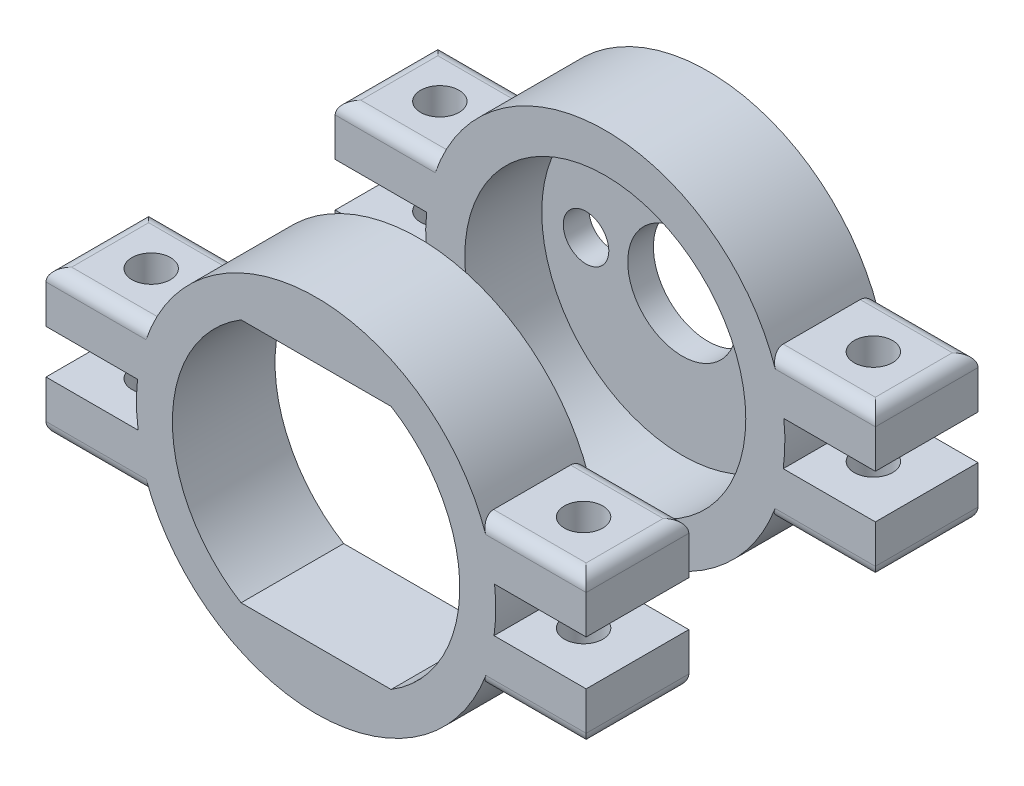
SolidWorks part; units mm, degrees
ref_plane "Alzado" through (0, 0, 0) normal (0, 0, 1) x (1, 0, 0)
ref_plane "Planta" through (0, 0, 0) normal (0, 1, 0) x (1, 0, 0)
ref_plane "Vista lateral" through (0, 0, 0) normal (1, 0, 0) x (0, 0, -1)
sketch "Croquis1" plane through (0, 0, 0) normal (0, 0, 1) x (1, 0, 0)
  line L0 (0, 1.5054) -> (0, -1.9098) construction
  line L1 (-13.9188, 1.5054) -> (-24.0497, 1.5054)
  line L2 (-24.0497, 1.5054) -> (-24.0497, 5.5054)
  line L3 (-13.8691, -1.9098) -> (-24, -1.9098)
  line L4 (-24.0497, 5.5054) -> (-12.8697, 5.5054)
  line L5 (-24, -1.9098) -> (-24, -5.9098)
  line L6 (-24, -5.9098) -> (-12.82, -5.9098)
  line L7 (24, -5.9098) -> (12.82, -5.9098)
  line L8 (24.0497, 5.5054) -> (12.8697, 5.5054)
  line L9 (13.8691, -1.9098) -> (24, -1.9098)
  line L10 (13.9188, 1.5054) -> (24.0143, 1.5054)
  line L11 (24, -1.9098) -> (24, -5.9098)
  line L12 (24.0143, 1.5054) -> (24.0497, 5.5054)
  arc A0 (12.8697, 5.5054) -> (-12.8697, 5.5054) centre (0, 0) ccw
  arc A1 (-13.9188, 1.5054) -> (-13.8691, -1.9098) centre (0, 0) ccw
  arc A2 (-12.82, -5.9098) -> (12.82, -5.9098) centre (0, 0) ccw
  arc A3 (13.8691, -1.9098) -> (13.9188, 1.5054) centre (0, 0) ccw
  dimension "D1" = 14
  dimension "D2" = 10.1309
  dimension "D3" = 10.1309
  dimension "D4" = 11.18
  dimension "D5" = 11.18
  dimension "D6" = 4
  dimension "D7" = 4
  dimension "D8" = 4
  dimension "D9" = 24
  dimension "D10" = 24
  dimension "D11" = 24.0497
extrude "Saliente-Extruir1" add sketch "Croquis1" along normal blind 8
ref_plane "Plano1" through (0, 0, 22.54) normal (0, 0, 1) x (1, 0, 0)
sketch "Croquis2" plane through (0, 0, 8) normal (0, 0, 1) x (1, 0, 0)
  circle A0 centre (0, 0) radius 10.95
  dimension "D1" = 21.9
extrude "Cortar-Extruir1" cut sketch "Croquis2" against normal blind 6
sketch "Croquis3" plane through (0, 0, 2) normal (0, 0, 1) x (1, 0, 0)
  line L0 (0, 10.95) -> (0, -10.95) construction
  line L1 (-10.95, 0) -> (10.95, 0) construction
  circle A0 centre (0, 0) radius 4.25
  circle A1 centre (0, 0) radius 10.95 construction
  circle A4 centre (-7.5, 0) radius 1.775
  circle A5 centre (7.5, 0) radius 1.775
  dimension "D1" = 8.5
  dimension "D2" = 3.55
  dimension "D3" = 3.55
  dimension "D4" = 7.5
  dimension "D5" = 7.5
extrude "Cortar-Extruir2" cut sketch "Croquis3" against normal blind 3.5
sketch "Croquis6" plane through (0, 0, 22.54) normal (0, 0, 1) x (1, 0, 0)
  line L0 (-12.8697, 5.5054) -> (-24, 5.5054)
  line L1 (-24, 5.5054) -> (-24, 1.5054)
  line L2 (-24, 1.5054) -> (-13.9188, 1.5054)
  line L3 (12.82, -5.9098) -> (24, -5.9098) construction
  line L4 (24, -1.9098) -> (13.8691, -1.9098)
  line L5 (24, -5.9098) -> (24, -1.9098)
  line L6 (12.8331, 5.5902) -> (24, 5.5902)
  line L7 (24, 5.5902) -> (24, 1.5902)
  line L8 (24, 1.5902) -> (13.9094, 1.5902)
  line L9 (12.82, -5.9098) -> (24, -5.9098)
  line L10 (-24, -1.9098) -> (-13.8691, -1.9098)
  line L11 (-24, -5.9098) -> (-24, -1.9098)
  line L12 (-12.82, -5.9098) -> (-24, -5.9098)
  line L13 (-24, -5.9098) -> (-12.82, -5.9098) construction
  line L14 (-12.8697, 5.5054) -> (-24.0497, 5.5054) construction
  line L16 (-24.0497, 1.5054) -> (-13.9188, 1.5054) construction
  arc A0 (12.8331, 5.5902) -> (-12.8697, 5.5054) centre (0, 0) ccw
  arc A1 (12.8697, 5.5054) -> (-12.8697, 5.5054) centre (0, 0) ccw construction
  arc A2 (-12.82, -5.9098) -> (12.82, -5.9098) centre (0, 0) ccw construction
  arc A3 (12.82, -5.9098) -> (-12.82, -5.9098) centre (0, 0) cw
  arc A4 (-13.9188, 1.5054) -> (-13.8691, -1.9098) centre (0, 0) ccw
  arc A5 (13.8691, -1.9098) -> (13.9094, 1.5902) centre (0, 0) ccw
  circle A6 centre (0, 0) radius 10.95 construction
  dimension "D5" = 0
  dimension "D6" = 3.5
  dimension "D10" = 14
  dimension "D14" = 0
  dimension "D15" = 0
  dimension "D1" = 4
  dimension "D2" = 4
  dimension "D3" = 10.1309
  dimension "D4" = 11.18
  dimension "D7" = 4
  dimension "D8" = 11.18
  dimension "D9" = 4
  dimension "D11" = 4
  dimension "D12" = 0
  dimension "D13" = 24
  dimension "D16" = 24
  dimension "D17" = 0
  dimension "D18" = 0
extrude "Saliente-Extruir3" add sketch "Croquis6" along normal blind 8
sketch "Croquis7" plane through (0, 0, 30.54) normal (0, 0, 1) x (1, 0, 0)
  line L0 (-5.8487, 9.5516) -> (5.8487, 9.5516)
  line L1 (-5.8487, -9.5516) -> (5.8487, -9.5516)
  arc A0 (-5.8487, 9.5516) -> (-5.8487, -9.5516) centre (0, 0) ccw
  arc A1 (5.8487, -9.5516) -> (5.8487, 9.5516) centre (0, 0) ccw
  dimension "D1" = 11.2
  dimension "D4" = 11.2
  dimension "D2" = 11.6974
  dimension "D3" = 11.6974
extrude "Cortar-Extruir8" cut sketch "Croquis7" against normal blind 10
sketch "Croquis8" plane through (0, 5.5054, 0) normal (0, 1, 0) x (1, 0, 0)
  line L6 (24.0497, 0) -> (12.8697, 0) construction
  line L7 (24, -30.54) -> (12.8331, -30.54) construction
  line L8 (0, -4) -> (0, -26.5) construction
  line L9 (-24.0497, -8) -> (-24.0497, 0) construction
  line L10 (-24, -30.54) -> (-24, -22.54) construction
  circle A0 centre (16.85, -26.54) radius 1.5
  circle A1 centre (16.8949, -4) radius 1.5
  circle A2 centre (-16.8949, -4) radius 1.5
  circle A3 centre (-16.85, -26.54) radius 1.5
  dimension "D1" = 3
  dimension "D2" = 3
  dimension "D5" = 4
  dimension "D6" = 4
  dimension "D7" = 7.1548
  dimension "D8" = 7.15
sketch "Croquis11" plane through (0, 5.5054, 0) normal (0, 1, 0) x (1, 0, 0)
  line L0 (-12.8697, -30.54) -> (-24, -30.54) construction
  line L1 (-24.0497, 0) -> (-21.0497, 0)
  line L2 (-24.0497, 0) -> (-24.0497, -30.54)
  line L3 (-24.0497, -30.54) -> (-21.0497, -30.54)
  line L4 (-21.0497, 0) -> (-21.0497, -30.54)
  line L5 (24, -30.54) -> (12.8331, -30.54) construction
  line L6 (24.0497, 0) -> (21.0497, 0)
  line L7 (24.0497, 0) -> (24.0497, -30.54)
  line L8 (24.0497, -30.54) -> (21.0497, -30.54)
  line L9 (21.0497, 0) -> (21.0497, -30.54)
  dimension "D1" = 3
  dimension "D2" = 3
extrude "Cortar-Extruir9" cut sketch "Croquis11" against normal through all both and the other way through all
extrude "Cortar-Extruir10" cut sketch "Croquis8" against normal through all both and the other way through all
fillet "Redondeo1" radius 1 12 edges at (16.9597, 5.5054, 0) (21.0497, 5.5054, 4) (16.9597, 5.5054, 8) (-16.9597, 5.5054, 0) (-21.0497, 5.5054, 4) (-16.9597, 5.5054, 8) (16.9349, -5.9098, 0) (16.9349, -5.9098, 8) (21.0497, -5.9098, 4) (-16.9349, -5.9098, 8) (-21.0497, -5.9098, 4) (-16.9349, -5.9098, 0)
fillet "Redondeo2" radius 1 12 edges at (16.9414, 5.5902, 22.54) (21.0497, 5.5902, 26.54) (16.9414, 5.5902, 30.54) (-16.9597, 5.5054, 22.54) (-21.0497, 5.5054, 26.54) (-16.9597, 5.5054, 30.54) (16.9349, -5.9098, 22.54) (21.0497, -5.9098, 26.54) (16.9349, -5.9098, 30.54) (-16.9349, -5.9098, 30.54) (-16.9349, -5.9098, 22.54) (-21.0497, -5.9098, 26.54)
